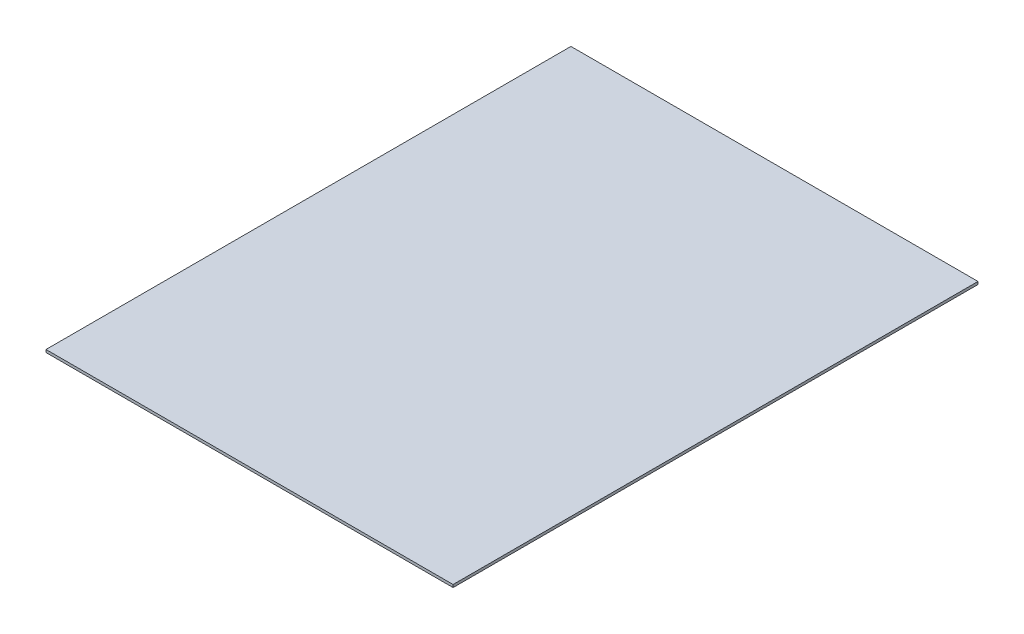
SolidWorks part; units mm, degrees
ref_plane "Front Plane" through (0, 0, 0) normal (0, 0, 1) x (1, 0, 0)
ref_plane "Top Plane" through (0, 0, 0) normal (0, 1, 0) x (1, 0, 0)
ref_plane "Right Plane" through (0, 0, 0) normal (1, 0, 0) x (0, 0, -1)
sketch "Sketch1" plane through (0, 0, 0) normal (0, 1, 0) x (1, 0, 0)
  line L1 (-241.3, -311.15) -> (241.3, -311.15)
  line L2 (-241.3, -311.15) -> (-241.3, 311.15)
  line L3 (-241.3, 311.15) -> (241.3, 311.15)
  line L4 (241.3, -311.15) -> (241.3, 311.15)
  line L5 (-241.3, -311.15) -> (241.3, 311.15) construction
  line L6 (-241.3, 311.15) -> (241.3, -311.15) construction
  point P0 (0, 0)
  dimension "D1" = 622.3
  dimension "D2" = 482.6
extrude "Boss-Extrude1" add sketch "Sketch1" along normal blind 3.175
